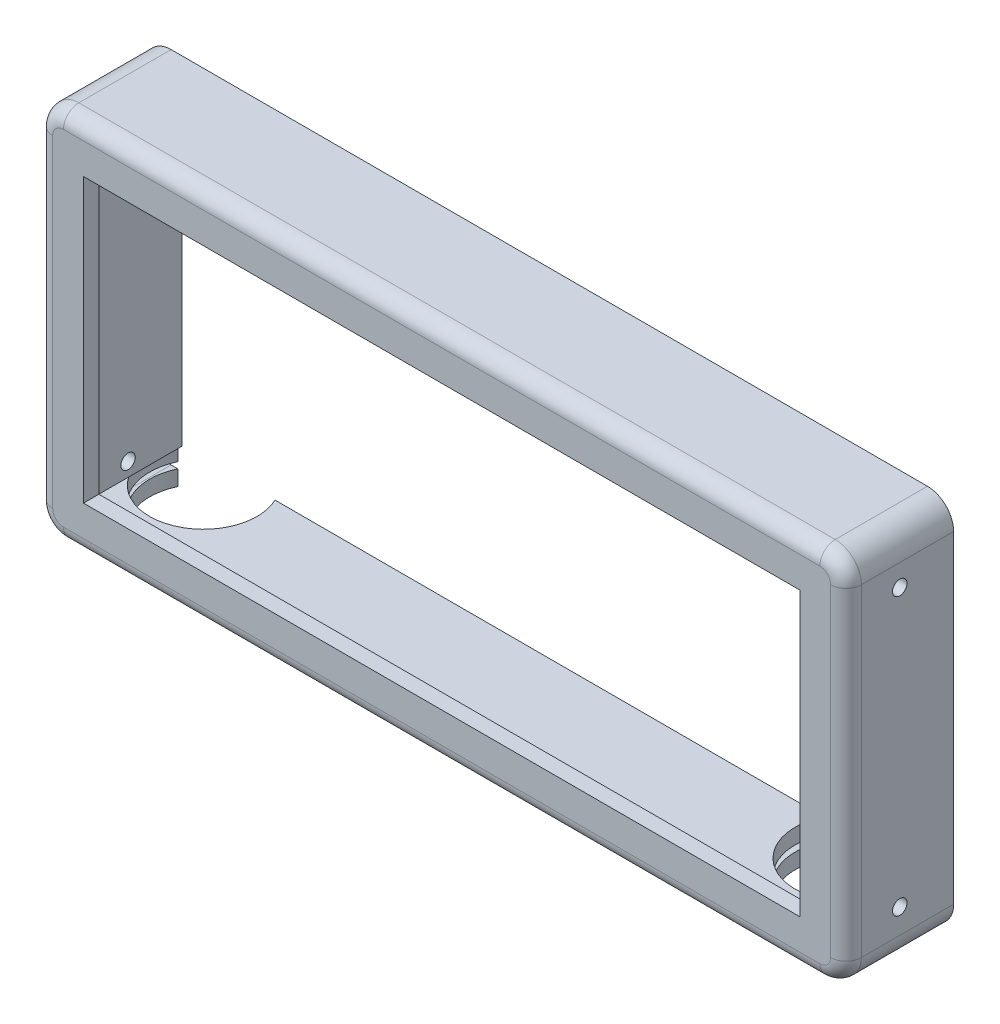
SolidWorks part; units mm, degrees
material "ABS"
ref_plane "Front Plane" through (0, 0, 0) normal (0, 0, 1) x (1, 0, 0)
ref_plane "Top Plane" through (0, 0, 0) normal (0, 1, 0) x (1, 0, 0)
ref_plane "Right Plane" through (0, 0, 0) normal (1, 0, 0) x (0, 0, -1)
sketch "Sketch1" plane through (0, 0, 0) normal (0, 0, 1) x (1, 0, 0)
  line L1 (-124.5, -54) -> (124.5, -54)
  line L2 (-124.5, -54) -> (-124.5, 54)
  line L3 (-124.5, 54) -> (124.5, 54)
  line L4 (124.5, -54) -> (124.5, 54)
  line L5 (-124.5, -54) -> (124.5, 54) construction
  line L6 (-124.5, 54) -> (124.5, -54) construction
  line L7 (119.5, 49) -> (-119.5, 49)
  line L8 (119.5, 49) -> (119.5, -49)
  line L9 (119.5, -49) -> (-119.5, -49)
  line L10 (-119.5, 49) -> (-119.5, -49)
  line L11 (-126.5, -56) -> (126.5, -56)
  line L12 (-126.5, -56) -> (-126.5, 56)
  line L13 (-126.5, 56) -> (126.5, 56)
  line L14 (126.5, -56) -> (126.5, 56)
  line L15 (-126.5, -56) -> (126.5, 56) construction
  line L16 (-126.5, 56) -> (126.5, -56) construction
  line L17 (-131.5, -61) -> (131.5, -61)
  line L18 (-131.5, -61) -> (-131.5, 61)
  line L19 (-131.5, 61) -> (131.5, 61)
  line L20 (131.5, -61) -> (131.5, 61)
  line L21 (-131.5, -61) -> (131.5, 61) construction
  line L22 (-131.5, 61) -> (131.5, -61) construction
  point P0 (0, 0)
  point P10 (0, 0)
  point P15 (0, 0)
  dimension "D1" = 249
  dimension "D2" = 108
  dimension "D3" = 5
  dimension "D4" = 5
  dimension "D5" = 5
  dimension "D6" = 5
  dimension "D7" = 2
  dimension "D8" = 2
  dimension "D9" = 5
  dimension "D10" = 5
extrude "Boss-Extrude1" add sketch "Sketch1" along normal blind 30 contours L17 L20 L19 L18 L14 L11 L12 L13 | L1 L4 L3 L2 L10 L7 L8 L9
sketch "Sketch2" plane through (0, 0, 30) normal (0, 0, 1) x (1, 0, 0)
  line L1 (-131.5, -61) -> (131.5, -61)
  line L2 (-131.5, -61) -> (-131.5, 61)
  line L3 (-131.5, 61) -> (131.5, 61)
  line L4 (131.5, -61) -> (131.5, 61)
  line L5 (-131.5, -61) -> (131.5, 61) construction
  line L6 (-131.5, 61) -> (131.5, -61) construction
  point P0 (0, 0)
extrude "Boss-Extrude2" add sketch "Sketch2" along normal blind 5
fillet "Fillet1" radius 1.5 4 edges at (124.5, -54, 15) (-124.5, -54, 15) (-124.5, 54, 15) (124.5, 54, 15)
sketch "Sketch3" plane through (0, -61, 0) normal (0, -1, 0) x (-1, 0, 0)
  line L1 (131.5, -35) -> (-131.5, -35) construction
  circle A0 centre (105, -7.5) radius 17.5
  circle A1 centre (-105, -7.5) radius 17.5
  dimension "D1" = 105
  dimension "D5" = 35
  dimension "D2" = 105
  dimension "D3" = 27.5
  dimension "D4" = 27.5
extrude "Cut-Extrude1" cut sketch "Sketch3" against normal blind 12
fillet "Fillet2" radius 3.5 4 edges at (126.5, -56, 15) (126.5, 56, 15) (-126.5, 56, 15) (-126.5, -56, 15)
fillet "Fillet3" radius 8.5 4 edges at (-131.5, -61, 17.5) (131.5, -61, 17.5) (131.5, 61, 17.5) (-131.5, 61, 17.5)
fillet "Fillet4" radius 5 8 edges at (129.0104, 58.5104, 35) (131.5, 0, 35) (129.0104, -58.5104, 35) (0, -61, 35) (-129.0104, -58.5104, 35) (-131.5, 0, 35) (-129.0104, 58.5104, 35) (0, 61, 35)
sketch "Sketch4" plane through (131.5, 0, 0) normal (1, 0, 0) x (0, 0, -1)
  line L0 (-35, -61) -> (-35, 61) construction
  line L1 (-35, -61) -> (0, -61) construction
  circle A0 centre (-17.5, -44.5) radius 2.35
  circle A1 centre (-17.5, 45.5) radius 2.35
  dimension "D1" = 17.5
  dimension "D3" = 4.7
  dimension "D4" = 90
  dimension "D2" = 16.5
extrude "Cut-Extrude2" cut sketch "Sketch4" against normal blind 279
sketch "Sketch5" plane through (0, 0, 35) normal (0, 0, 1) x (1, 0, 0)
  line L0 (-126.5, 52.5) -> (-126.5, -52.5) construction
  line L1 (-116.5, -46) -> (116.5, -46)
  line L2 (-116.5, -46) -> (-116.5, 46)
  line L3 (-116.5, 46) -> (116.5, 46)
  line L4 (116.5, -46) -> (116.5, 46)
  line L5 (-116.5, -46) -> (116.5, 46) construction
  line L6 (-116.5, 46) -> (116.5, -46) construction
  line L7 (123, 56) -> (-123, 56) construction
  point P0 (0, 0)
  dimension "D1" = 10
  dimension "D2" = 10
extrude "Cut-Extrude3" cut sketch "Sketch5" against normal blind 10
